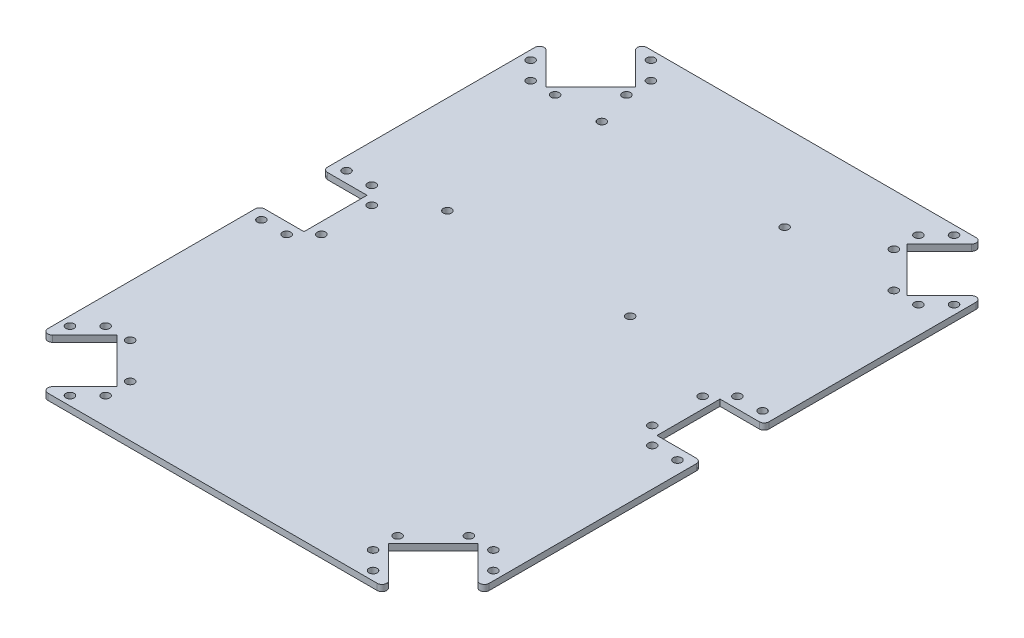
SolidWorks part; units mm, degrees
ref_plane "Front Plane" through (0, 0, 0) normal (0, 0, 1) x (1, 0, 0)
ref_plane "Top Plane" through (0, 0, 0) normal (0, 1, 0) x (1, 0, 0)
ref_plane "Right Plane" through (0, 0, 0) normal (1, 0, 0) x (0, 0, -1)
sketch "Sketch2" plane through (0, 0, 0) normal (0, 1, 0) x (1, 0, 0)
  line L0 (-70, 0) -> (70, 0) construction
  line L1 (-70, 95) -> (70, 95)
  line L2 (-70, 95) -> (-70, -95)
  line L3 (-70, -95) -> (70, -95)
  line L4 (70, 95) -> (70, -95)
  line L5 (70, 95) -> (0, 25) construction
  line L7 (0, 95) -> (0, -95) construction
  line L8 (42.4228, 78.7365) -> (38.5337, 82.6256) construction
  line L9 (38.5337, 82.6256) -> (42.4228, 86.5147) construction
  line L10 (42.4228, 86.5147) -> (48.0797, 92.1716) construction
  line L11 (48.0797, 92.1716) -> (50.9081, 95) construction
  circle A5 centre (42.4228, 78.7365) radius 1.3
  circle A6 centre (42.4228, 86.5147) radius 1.3
  circle A7 centre (48.0797, 92.1716) radius 1.3
  circle A8 centre (66, 13.5) radius 1.3
  circle A9 centre (58, 13.5) radius 1.3
  circle A10 centre (52.5, 8) radius 1.3
  circle A11 centre (52.5, -8) radius 1.3
  circle A12 centre (58, -13.5) radius 1.3
  circle A13 centre (66, -13.5) radius 1.3
  circle A14 centre (67.1716, 73.0797) radius 1.3
  circle A15 centre (61.5147, 67.4228) radius 1.3
  circle A16 centre (53.7365, 67.4228) radius 1.3
  circle A17 centre (67.1716, -73.0797) radius 1.3
  circle A18 centre (61.5147, -67.4228) radius 1.3
  circle A19 centre (53.7365, -67.4228) radius 1.3
  circle A20 centre (48.0797, -92.1716) radius 1.3
  circle A21 centre (42.4228, -86.5147) radius 1.3
  circle A22 centre (42.4228, -78.7365) radius 1.3
  circle A23 centre (-48.0797, 92.1716) radius 1.3
  circle A24 centre (-42.4228, 86.5147) radius 1.3
  circle A25 centre (-42.4228, 78.7365) radius 1.3
  circle A26 centre (-67.1716, 73.0797) radius 1.3
  circle A27 centre (-61.5147, 67.4228) radius 1.3
  circle A28 centre (-53.7365, 67.4228) radius 1.3
  circle A29 centre (-67.1716, -73.0797) radius 1.3
  circle A30 centre (-61.5147, -67.4228) radius 1.3
  circle A31 centre (-53.7365, -67.4228) radius 1.3
  circle A32 centre (-42.4228, -78.7365) radius 1.3
  circle A33 centre (-42.4228, -86.5147) radius 1.3
  circle A34 centre (-48.0797, -92.1716) radius 1.3
  circle A35 centre (-52.5, -8) radius 1.3
  circle A36 centre (-58, -13.5) radius 1.3
  circle A37 centre (-66, -13.5) radius 1.3
  circle A38 centre (-66, 13.5) radius 1.3
  circle A39 centre (-58, 13.5) radius 1.3
  circle A40 centre (-52.5, 8) radius 1.3
  point P0 (0, 0)
  point P27 (0, 0)
  dimension "D6" = 5.5
  dimension "D10" = 8
  dimension "D11" = 5.5
  dimension "D2" = 2.6
  dimension "D3" = 8
  dimension "D4" = 4
  dimension "D5" = 5.5
  dimension "D7" = 45
  dimension "D8" = 140
  dimension "D9" = 190
  dimension "D12" = 5.5
  dimension "D13" = 8
  dimension "D14" = 4
  dimension "D15" = 8
extrude "Boss-Extrude1" add sketch "Sketch2" along normal blind 2
sketch "Sketch3" plane through (0, 2, 0) normal (0, 1, 0) x (1, 0, 0)
  line L0 (0, -95) -> (0, 95) construction
  line L1 (-70, -95) -> (70, -95) construction
  line L2 (70, 95) -> (-70, 95) construction
  line L3 (-70, 0) -> (70, 0) construction
  line L4 (-70, 95) -> (-70, -95) construction
  line L5 (70, -95) -> (70, 95) construction
  line L6 (70, 95) -> (0, 25) construction
  line L7 (70, -10) -> (56, -10)
  line L8 (70, -10) -> (70, 10)
  line L9 (70, 10) -> (56, 10)
  line L10 (56, -10) -> (56, 10)
  line L11 (55.8579, 95) -> (43.1299, 82.2721)
  line L12 (43.1299, 82.2721) -> (57.2721, 68.1299)
  line L13 (57.2721, 68.1299) -> (70, 80.8579)
  line L14 (70, 80.8579) -> (70, 95)
  line L15 (70, 95) -> (55.8579, 95)
  line L16 (70, -80.8579) -> (70, -95)
  line L17 (57.2721, -68.1299) -> (70, -80.8579)
  line L18 (43.1299, -82.2721) -> (57.2721, -68.1299)
  line L19 (55.8579, -95) -> (43.1299, -82.2721)
  line L20 (70, -95) -> (55.8579, -95)
  line L21 (-70, 80.8579) -> (-70, 95)
  line L22 (-57.2721, 68.1299) -> (-70, 80.8579)
  line L23 (-43.1299, 82.2721) -> (-57.2721, 68.1299)
  line L24 (-55.8579, 95) -> (-43.1299, 82.2721)
  line L25 (-70, 95) -> (-55.8579, 95)
  line L26 (-70, 10) -> (-56, 10)
  line L27 (-56, -10) -> (-56, 10)
  line L28 (-70, -10) -> (-56, -10)
  line L29 (-70, -10) -> (-70, 10)
  line L30 (-57.2721, -68.1299) -> (-70, -80.8579)
  line L31 (-43.1299, -82.2721) -> (-57.2721, -68.1299)
  line L32 (-55.8579, -95) -> (-43.1299, -82.2721)
  line L33 (-70, -95) -> (-55.8579, -95)
  line L34 (-70, -80.8579) -> (-70, -95)
  dimension "D1" = 10
  dimension "D2" = 20
  dimension "D3" = 14
  dimension "D4" = 45
  dimension "D5" = 18
  dimension "D6" = 20
  dimension "D7" = 10
extrude "Cut-Extrude1" cut sketch "Sketch3" against normal up to surface (2 mm away) up to face at (0, 0, 0)
fillet "Fillet1" radius 1.5 12 edges at (-70, 1, 10) (-70, 1, -10) (-70, 1, 80.8579) (-55.8579, 1, 95) (55.8579, 1, 95) (70, 1, 80.8579) (70, 1, 10) (70, 1, -10) (70, 1, -80.8579) (55.8579, 1, -95) (-70, 1, -80.8579) (-55.8579, 1, -95)
sketch "Sketch4" plane through (0, 2, 0) normal (0, 1, 0) x (1, 0, 0)
  line L1 (-39, 67.5) -> (19, 67.5) construction
  line L2 (-39, 67.5) -> (-39, 18.5) construction
  line L3 (-39, 18.5) -> (19, 18.5) construction
  line L4 (19, 67.5) -> (19, 18.5) construction
  line L5 (-42.5, 71) -> (42.5, 71) construction
  line L6 (-42.5, 71) -> (-42.5, 15) construction
  line L7 (-42.5, 15) -> (42.5, 15) construction
  line L8 (42.5, 71) -> (42.5, 15) construction
  line L9 (52.2365, 95) -> (-52.2365, 95) construction
  line L10 (-70, 77.2365) -> (-70, 11.5) construction
  circle A0 centre (-39, 67.5) radius 1.3
  circle A1 centre (19, 67.5) radius 1.3
  circle A2 centre (19, 18.5) radius 1.3
  circle A3 centre (-39, 18.5) radius 1.3
  dimension "D1" = 2.6
  dimension "D2" = 58
  dimension "D3" = 85
  dimension "D4" = 56
  dimension "D5" = 49
  dimension "D6" = 3.5
  dimension "D7" = 3.5
  dimension "D8" = 3.5
  dimension "D9" = 24
  dimension "D10" = 27.5
extrude "Cut-Extrude2" cut sketch "Sketch4" against normal up to surface (2 mm away) up to face at (0, 0, 0)
